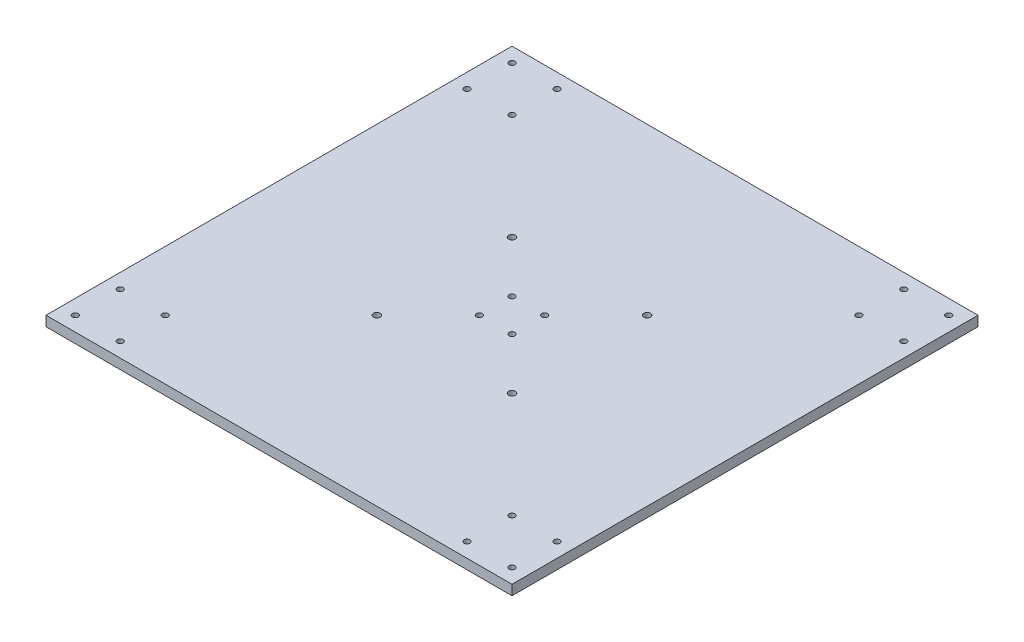
SolidWorks part; units mm, degrees
ref_plane "Front Plane" through (0, 0, 0) normal (0, 0, 1) x (1, 0, 0)
ref_plane "Top Plane" through (0, 0, 0) normal (0, 1, 0) x (1, 0, 0)
ref_plane "Right Plane" through (0, 0, 0) normal (1, 0, 0) x (0, 0, -1)
sketch "Sketch1" plane through (0, 0, 0) normal (0, 1, 0) x (1, 0, 0)
  line L0 (104.0003, -130.9497) -> (130.9497, -130.9497) construction
  line L1 (-139.7, -139.7) -> (139.7, -139.7)
  line L2 (-139.7, -139.7) -> (-139.7, 139.7)
  line L3 (-139.7, 139.7) -> (139.7, 139.7)
  line L4 (139.7, -139.7) -> (139.7, 139.7)
  line L5 (-139.7, -139.7) -> (139.7, 139.7) construction
  line L6 (-139.7, 139.7) -> (139.7, -139.7) construction
  line L7 (-117.475, 117.475) -> (117.475, 117.475) construction
  line L8 (-117.475, 117.475) -> (-117.475, -117.475) construction
  line L9 (-117.475, -117.475) -> (117.475, -117.475) construction
  line L10 (117.475, 117.475) -> (117.475, -117.475) construction
  line L11 (-117.475, 117.475) -> (117.475, -117.475) construction
  line L12 (-117.475, -117.475) -> (117.475, 117.475) construction
  line L13 (-130.9497, -130.9497) -> (-104.0003, -130.9497) construction
  line L14 (-130.9497, -130.9497) -> (-130.9497, -104.0003) construction
  line L15 (-130.9497, -104.0003) -> (-104.0003, -104.0003) construction
  line L16 (-104.0003, -130.9497) -> (-104.0003, -104.0003) construction
  line L17 (-130.9497, -130.9497) -> (-104.0003, -104.0003) construction
  line L18 (-130.9497, -104.0003) -> (-104.0003, -130.9497) construction
  line L19 (104.0003, -130.9497) -> (104.0003, -104.0003) construction
  line L20 (104.0003, -104.0003) -> (130.9497, -104.0003) construction
  line L21 (130.9497, -130.9497) -> (130.9497, -104.0003) construction
  line L22 (104.0003, -130.9497) -> (130.9497, -104.0003) construction
  line L23 (104.0003, -104.0003) -> (130.9497, -130.9497) construction
  line L25 (104.0003, 104.0003) -> (130.9497, 104.0003) construction
  line L26 (104.0003, 104.0003) -> (104.0003, 130.9497) construction
  line L27 (104.0003, 130.9497) -> (130.9497, 130.9497) construction
  line L28 (130.9497, 104.0003) -> (130.9497, 130.9497) construction
  line L29 (104.0003, 104.0003) -> (130.9497, 130.9497) construction
  line L30 (104.0003, 130.9497) -> (130.9497, 104.0003) construction
  line L31 (-130.9497, 104.0003) -> (-104.0003, 104.0003) construction
  line L32 (-130.9497, 104.0003) -> (-130.9497, 130.9497) construction
  line L33 (-130.9497, 130.9497) -> (-104.0003, 130.9497) construction
  line L34 (-104.0003, 104.0003) -> (-104.0003, 130.9497) construction
  line L35 (-130.9497, 104.0003) -> (-104.0003, 130.9497) construction
  line L36 (-130.9497, 130.9497) -> (-104.0003, 104.0003) construction
  line L38 (-9.779, 9.779) -> (9.779, 9.779) construction
  line L39 (-9.779, 9.779) -> (-9.779, -9.779) construction
  line L40 (-9.779, -9.779) -> (9.779, -9.779) construction
  line L41 (-42.8642, -42.8642) -> (42.8642, 42.8642) construction
  line L42 (-42.8642, 42.8642) -> (42.8642, -42.8642) construction
  line L43 (-40.513, -40.513) -> (40.513, -40.513) construction
  line L44 (-40.513, -40.513) -> (-40.513, 40.513) construction
  line L45 (-40.513, 40.513) -> (40.513, 40.513) construction
  line L46 (40.513, -40.513) -> (40.513, 40.513) construction
  line L47 (-40.513, -40.513) -> (40.513, 40.513) construction
  line L48 (-40.513, 40.513) -> (40.513, -40.513) construction
  line L49 (9.779, 9.779) -> (9.779, -9.779) construction
  line L50 (-9.779, 9.779) -> (9.779, -9.779) construction
  line L51 (-9.779, -9.779) -> (9.779, 9.779) construction
  circle A0 centre (-130.9497, -130.9497) radius 1.778
  circle A1 centre (-104.0003, -130.9497) radius 1.778
  circle A2 centre (-130.9497, -104.0003) radius 1.778
  circle A3 centre (-104.0003, -104.0003) radius 1.778
  circle A4 centre (104.0003, -130.9497) radius 1.778
  circle A5 centre (130.9497, -130.9497) radius 1.778
  circle A6 centre (104.0003, -104.0003) radius 1.778
  circle A7 centre (130.9497, -104.0003) radius 1.778
  circle A8 centre (104.0003, 104.0003) radius 1.778
  circle A9 centre (130.9497, 104.0003) radius 1.778
  circle A10 centre (104.0003, 130.9497) radius 1.778
  circle A11 centre (130.9497, 130.9497) radius 1.778
  circle A12 centre (-130.9497, 104.0003) radius 1.778
  circle A13 centre (-104.0003, 104.0003) radius 1.778
  circle A14 centre (-130.9497, 130.9497) radius 1.778
  circle A15 centre (-104.0003, 130.9497) radius 1.778
  circle A16 centre (-9.779, -9.779) radius 1.778
  circle A17 centre (-40.513, 40.513) radius 2.032
  circle A18 centre (40.513, 40.513) radius 2.032
  circle A19 centre (-40.513, -40.513) radius 2.032
  circle A20 centre (40.513, -40.513) radius 2.032
  circle A21 centre (9.779, -9.779) radius 1.778
  circle A22 centre (-9.779, 9.779) radius 1.778
  circle A23 centre (9.779, 9.779) radius 1.778
  point P0 (0, 0)
  point P6 (0, 0)
  point P11 (0, 0)
  point P50 (0, 0)
  dimension "D1" = 22.225
extrude "Boss-Extrude1" add sketch "Sketch1" along normal blind 5.9944
